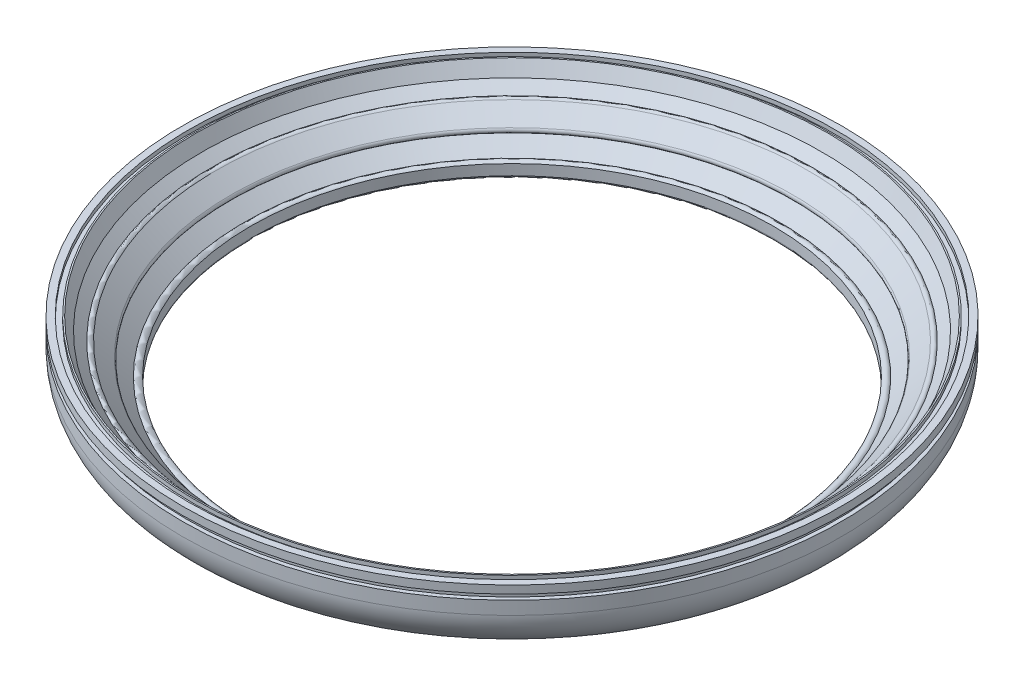
SolidWorks part; units mm, degrees
ref_plane "Front Plane" through (0, 0, 0) normal (0, 0, 1) x (1, 0, 0)
ref_plane "Top Plane" through (0, 0, 0) normal (0, 1, 0) x (1, 0, 0)
ref_plane "Right Plane" through (0, 0, 0) normal (1, 0, 0) x (0, 0, -1)
sketch "Sketch1" plane through (0, 0, 0) normal (0, 0, 1) x (1, 0, 0)
  line L0 (0, 0) -> (-25, 0) construction
  line L1 (0, 2.809) -> (0, 0) construction
  line L2 (-25, 0) -> (-25, 4)
  line L3 (-25, 4) -> (-24.7, 4)
  line L4 (-24.7, 4) -> (-24.7, 4.4)
  line L5 (-24.7, 4.4) -> (-25, 4.4)
  line L6 (-24.5021, 5) -> (-25, 5)
  line L7 (-25, 5) -> (-25, 4.4)
  line L8 (-24.5021, 5) -> (-24.5021, 4.7)
  line L9 (-24.5021, 4.7) -> (-24.1031, 4.7)
  line L10 (-24.1031, 4.7) -> (-24.1031, 5)
  line L11 (-24.1031, 5) -> (-23.9986, 5)
  line L12 (-23.9986, 5) -> (-23.5247, 4.0073)
  line L13 (-25, 0) -> (-19.8175, 0)
  line L14 (-19.8175, 0) -> (-19.8175, 1)
  line L19 (-20.313, 0.9999) -> (-21.327, 1.9494)
  line L23 (-22.8132, 3.341) -> (-23.5247, 4.0073)
  line L24 (-22.4485, 3.341) -> (-21.327, 2.2909)
  arc A0 (-20.313, 0.9999) -> (-19.8175, 1) centre (-20.0652, 0.7678) cw
  arc A7 (-22.4485, 3.341) -> (-22.8132, 3.341) centre (-22.6309, 3.1587) ccw
  arc A8 (-21.327, 2.2909) -> (-21.327, 1.9494) centre (-21.4978, 2.1201) cw
revolve "Revolve1" add sketch "Sketch1" angle 360 about L1
fillet "Fillet1" radius 3 1 edges at (0, 0, 25)
fillet "Fillet2" radius 0.2 1 edges at (0, 0, 19.8175)
sketch "Sketch2" plane through (0, 0, 0) normal (0, 1, 0) x (1, 0, 0)
  line L0 (25, 0) -> (0, 0) construction
  line L1 (0, 0) -> (-25, 0) construction
  line L2 (0, 0) -> (0, 25) construction
  line L3 (0, 0) -> (0, -25) construction
  line L4 (25, 0) -> (25, 2)
  line L5 (25, 0) -> (25, -2)
  line L6 (-25, 0) -> (-25, 2)
  line L7 (-25, 0) -> (-25, -2)
  line L8 (0, 25) -> (-2, 25)
  line L9 (0, 25) -> (2, 25)
  line L10 (0, -25) -> (-2, -25)
  line L11 (0, -25) -> (2, -25)
sketch "Sketch3" plane through (0, 0, 0) normal (1, 0, 0) x (0, 0, -1)
  line L0 (-21.8, 0) -> (-21.8, 4)
  line L1 (0, 0) -> (-25, 0) construction
  line L2 (21.8, 0) -> (21.8, 0.8193)
  line L3 (0, 0) -> (25, 0) construction
sketch "Sketch4" plane through (0, 0, 0) normal (1, 0, 0) x (0, 0, -1)
  line L0 (-25, 0) -> (-25, 2.5)
  line L2 (0, 0) -> (-25, 0) construction
  line L3 (-25, 2.5) -> (-25, 5)
  line L4 (-25, 2.5) -> (-25, 3.75)
  line L5 (0, 0) -> (25, 0) construction
  line L7 (25, 0) -> (25, 5)
  line L8 (25, 2.5) -> (25, 3.8827)
sketch "Sketch5" plane through (0, 0, 0) normal (0, 0, 1) x (1, 0, 0)
  line L0 (25, 0) -> (25, 3)
  line L2 (25, 0) -> (0, 0) construction
  line L3 (25, 3) -> (25, 4) construction
  line L4 (-25, 3) -> (25, 3) construction
  line L5 (25, 3) -> (25, 5)
  line L6 (-25, 0) -> (-25, 3)
  line L7 (0, 0) -> (-25, 0) construction
  line L8 (-25, 3) -> (-25, 5)
